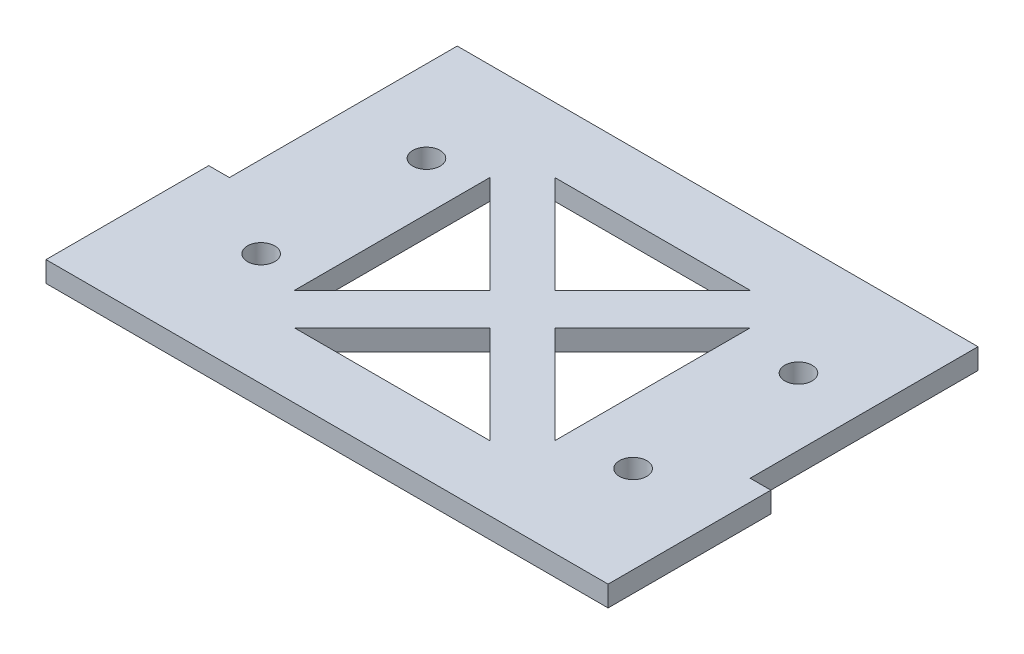
SolidWorks part; units mm, degrees
ref_plane "Alzado" through (0, 0, 0) normal (0, 0, 1) x (1, 0, 0)
ref_plane "Planta" through (0, 0, 0) normal (0, 1, 0) x (1, 0, 0)
ref_plane "Vista lateral" through (0, 0, 0) normal (1, 0, 0) x (0, 0, -1)
sketch "Sketch1" plane through (0, 0, 0) normal (0, 1, 0) x (1, 0, 0)
  line L1 (-43.175, -30) -> (43.175, -30)
  line L2 (-43.175, -30) -> (-43.175, 30)
  line L3 (-43.175, 30) -> (43.175, 30)
  line L4 (43.175, -30) -> (43.175, 30)
  line L5 (-43.175, -30) -> (43.175, 30) construction
  line L6 (-43.175, 30) -> (43.175, -30) construction
  line L7 (-43.175, 30) -> (-40, 30)
  line L8 (-43.175, 30) -> (-43.175, -5)
  line L9 (-43.175, -5) -> (-40, -5)
  line L10 (-40, 30) -> (-40, -5)
  line L11 (-43.175, 30) -> (-40, -5) construction
  line L12 (-43.175, -5) -> (-40, 30) construction
  line L13 (43.175, 30) -> (40, 30)
  line L14 (43.175, 30) -> (43.175, -5)
  line L15 (43.175, -5) -> (40, -5)
  line L16 (40, 30) -> (40, -5)
  line L17 (43.175, 30) -> (40, -5) construction
  line L18 (43.175, -5) -> (40, 30) construction
  point P0 (0, 0)
  point P9 (-41.5875, 12.5)
  point P13 (41.5875, 12.5)
  point P14 (0, 0)
  dimension "D1" = 86.35
  dimension "D2" = 60
  dimension "D3" = 3.175
  dimension "D4" = 25
extrude "Boss-Extrude1" add sketch "Sketch1" along normal blind 3.175 contours L16 L3 L10 L9 L2 L1 L4 L15
sketch "Sketch2" plane through (0, 3.175, 0) normal (0, 1, 0) x (1, 0, 0)
  line L1 (-27.43, -12.7) -> (29.72, -12.7) construction
  line L2 (-27.43, -12.7) -> (-27.43, 12.7) construction
  line L3 (-27.43, 12.7) -> (29.72, 12.7) construction
  line L4 (29.72, -12.7) -> (29.72, 12.7) construction
  line L5 (-27.43, -12.7) -> (29.72, 12.7) construction
  line L6 (-27.43, 12.7) -> (29.72, -12.7) construction
  line L7 (40, 30) -> (40, -5) construction
  circle A0 centre (-27.43, 12.7) radius 2.1
  circle A1 centre (29.72, 12.7) radius 2.1
  circle A2 centre (29.72, -12.7) radius 2.1
  circle A3 centre (-27.43, -12.7) radius 2.1
  point P0 (0, 0)
  point P10 (-27.43, 0)
  point P14 (0, 0)
  point P15 (-24.8785, -12.7)
  dimension "D4" = 4.2
  dimension "D1" = 10.28
  dimension "D2" = 67.43
  dimension "D3" = 25.4
extrude "Cut-Extrude1" cut sketch "Sketch2" against normal blind 3.175
sketch "Sketch3" plane through (0, 3.175, 0) normal (0, 1, 0) x (1, 0, 0)
  line L0 (-20, -15) -> (-20, 15)
  line L1 (-20, 15) -> (-5, 0)
  line L2 (-5, 0) -> (-20, -15)
  line L6 (0, 5) -> (-15, 20)
  line L7 (-15, 20) -> (15, 20)
  line L8 (15, 20) -> (0, 5)
  line L9 (5, 0) -> (20, 15)
  line L10 (20, 15) -> (20, -15)
  line L11 (20, -15) -> (5, 0)
  line L12 (0, -5) -> (15, -20)
  line L13 (15, -20) -> (-15, -20)
  line L14 (-15, -20) -> (0, -5)
  point P2 (-20, 0)
  point P4 (0, 0)
  point P17 (0, 0)
  dimension "D1" = 30
  dimension "D2" = 15
  dimension "D4" = 5
  dimension "D3" = 4
extrude "Cut-Extrude2" cut sketch "Sketch3" against normal blind 3.175
